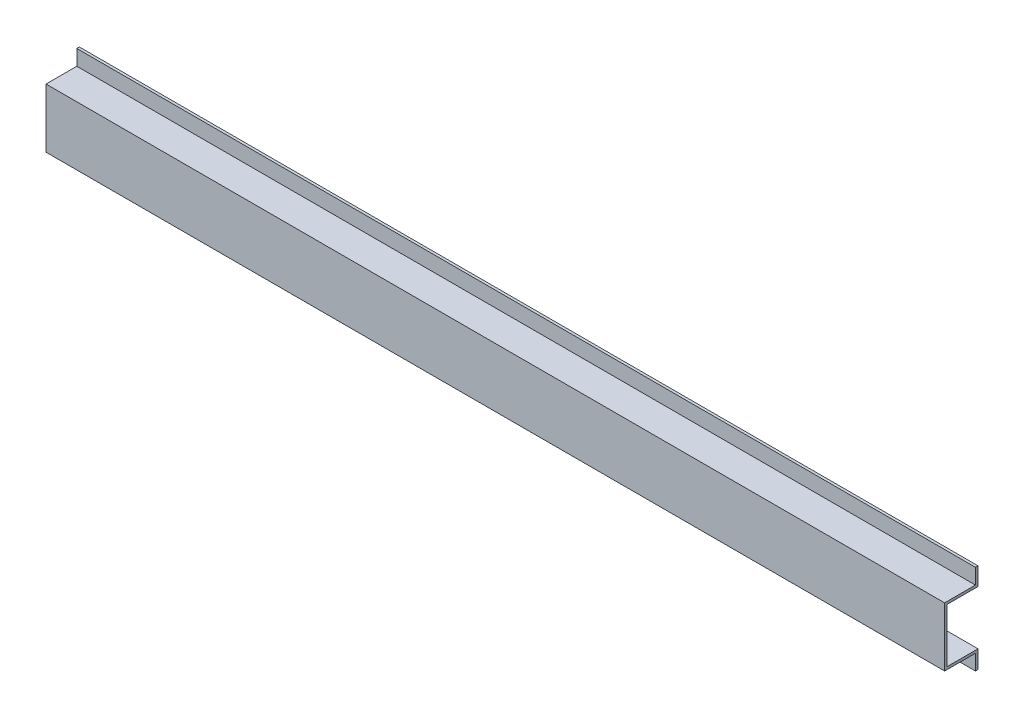
SolidWorks part; units mm, degrees
ref_plane "Alzado" through (0, 0, 0) normal (0, 0, 1) x (1, 0, 0)
ref_plane "Planta" through (0, 0, 0) normal (0, 1, 0) x (1, 0, 0)
ref_plane "Vista lateral" through (0, 0, 0) normal (1, 0, 0) x (0, 0, -1)
sketch "Croquis1" plane through (0, 0, 0) normal (1, 0, 0) x (0, 0, -1)
  line L0 (0, 0) -> (0, -7)
  line L1 (0, -7) -> (-12, -7)
  line L2 (-12, -7) -> (-12, -28)
  line L3 (-12, -28) -> (0, -28)
  line L4 (0, -28) -> (0, -35)
  line L5 (-1, 0) -> (-1, -6)
  line L6 (-1, -6) -> (-13, -6)
  line L7 (-13, -6) -> (-13, -29)
  line L8 (-13, -29) -> (-1, -29)
  line L9 (-1, -29) -> (-1, -35)
  line L10 (0, 0) -> (-1, 0)
  line L11 (0, -35) -> (-1, -35)
  dimension "D1" = 7
  dimension "D2" = 7
  dimension "D3" = 35
  dimension "D4" = 12
  dimension "D5" = 1
extrude "Saliente-Extruir1" add sketch "Croquis1" along normal blind 350
